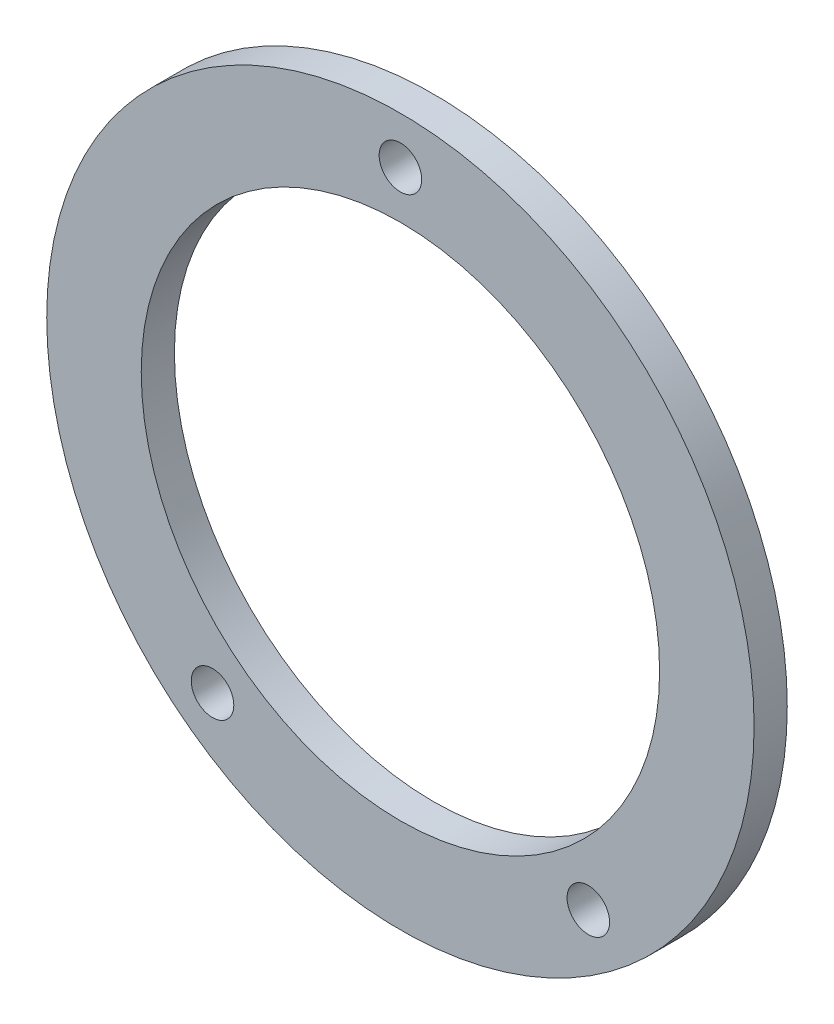
SolidWorks part; units mm, degrees
ref_plane "Plan de face" through (0, 0, 0) normal (0, 0, 1) x (1, 0, 0)
ref_plane "Plan de dessus" through (0, 0, 0) normal (0, 1, 0) x (1, 0, 0)
ref_plane "Plan de droite" through (0, 0, 0) normal (1, 0, 0) x (0, 0, -1)
sketch "Esquisse1" plane through (0, 0, 0) normal (0, 0, 1) x (1, 0, 0)
  line L0 (0, 27.75) -> (0, 0) construction
  line L1 (0, 0) -> (17, -21.9331) construction
  line L2 (0, 0) -> (-17, -21.9331) construction
  circle A0 centre (0, 0) radius 23.45
  circle A1 centre (0, 0) radius 32
  circle A2 centre (17, -21.9331) radius 1.925
  circle A3 centre (-17, -21.9331) radius 1.925
  circle A14 centre (0, 27.75) radius 1.925
  dimension "D1" = 46.9
  dimension "D2" = 64
  dimension "D3" = 3.85
  dimension "D4" = 27.75
  dimension "D5" = 142.221
  dimension "D6" = 142.221
extrude "Boss.-Extru.1" add sketch "Esquisse1" along normal blind 3
